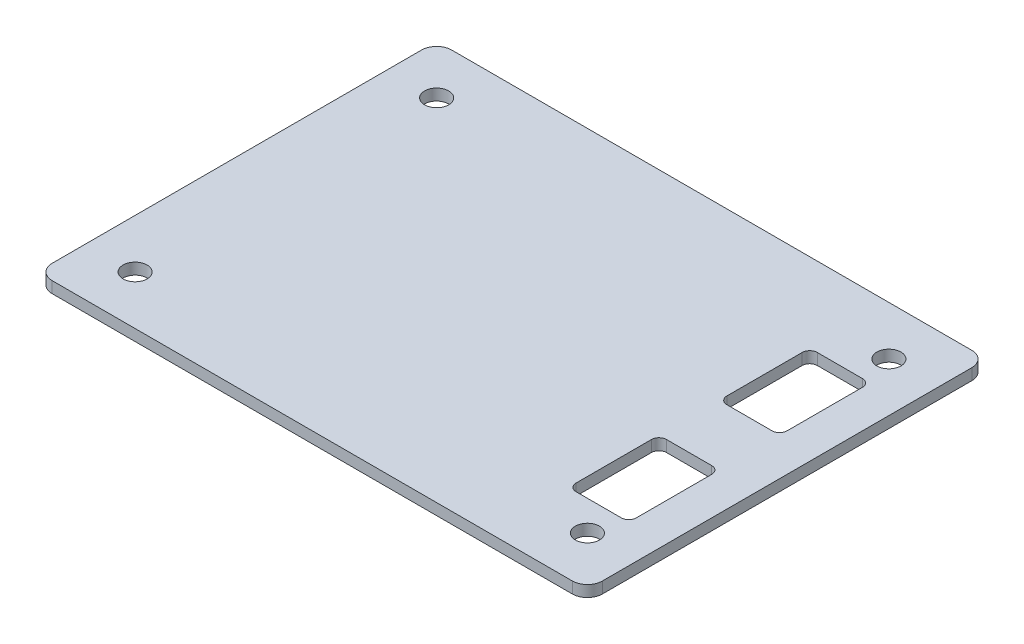
SolidWorks part; units mm, degrees
ref_plane "前视基准面" through (0, 0, 0) normal (0, 0, 1) x (1, 0, 0)
ref_plane "上视基准面" through (0, 0, 0) normal (0, 1, 0) x (1, 0, 0)
ref_plane "右视基准面" through (0, 0, 0) normal (1, 0, 0) x (0, 0, -1)
sketch "草图1" plane through (0, 0, 0) normal (0, 1, 0) x (1, 0, 0)
  line L1 (36.5, -26.5) -> (-36.5, -26.5)
  line L2 (36.5, -26.5) -> (36.5, 26.5)
  line L3 (36.5, 26.5) -> (-36.5, 26.5)
  line L4 (-36.5, -26.5) -> (-36.5, 26.5)
  line L5 (36.5, -26.5) -> (-36.5, 26.5) construction
  line L6 (36.5, 26.5) -> (-36.5, -26.5) construction
  point P0 (0, 0)
  dimension "D1" = 73
  dimension "D2" = 53
extrude "凸台-拉伸1" add sketch "草图1" along normal blind 1.5
fillet "圆角1" radius 2 4 edges at (-36.5, 0.75, -26.5) (36.5, 0.75, -26.5) (36.5, 0.75, 26.5) (-36.5, 0.75, 26.5)
sketch "草图2" plane through (0, 1.5, 0) normal (0, 1, 0) x (1, 0, 0)
  line L1 (30, -20) -> (-30, -20) construction
  line L2 (30, -20) -> (30, 20) construction
  line L3 (30, 20) -> (-30, 20) construction
  line L4 (-30, -20) -> (-30, 20) construction
  line L5 (30, -20) -> (-30, 20) construction
  line L6 (30, 20) -> (-30, -20) construction
  circle A0 centre (-30, 20) radius 1.6
  point P0 (0, 0)
  dimension "D3" = 3.2
  dimension "D1" = 60
  dimension "D2" = 40
extrude "切除-拉伸1" cut sketch "草图2" against normal through all
pattern_linear "阵列(线性)1" count 2 spacing 60 along (1, 0, 0) count 2 spacing 40 along (0, 0, 1) of "切除-拉伸1"
sketch "草图3" plane through (0, 1.5, 0) normal (0, 1, 0) x (1, 0, 0)
  line L0 (0, 0) -> (33.3449, 0) construction
  line L1 (36.5, -24.5) -> (36.5, 24.5) construction
  line L2 (23.5, 16) -> (31.5, 16)
  line L3 (23.5, 16) -> (23.5, 4)
  line L4 (23.5, 4) -> (31.5, 4)
  line L5 (31.5, 16) -> (31.5, 4)
  dimension "D1" = 8
  dimension "D2" = 12
  dimension "D3" = 5
  dimension "D4" = 4
extrude "切除-拉伸2" cut sketch "草图3" against normal through all contours L2 L5 L4 L3
fillet "圆角2" radius 1 4 edges at (31.5, 0.75, -4) (23.5, 0.75, -4) (23.5, 0.75, -16) (31.5, 0.75, -16)
pattern_linear "阵列(线性)2" count 2 spacing 20 along (0, 0, 1) of "圆角2", "切除-拉伸2"
